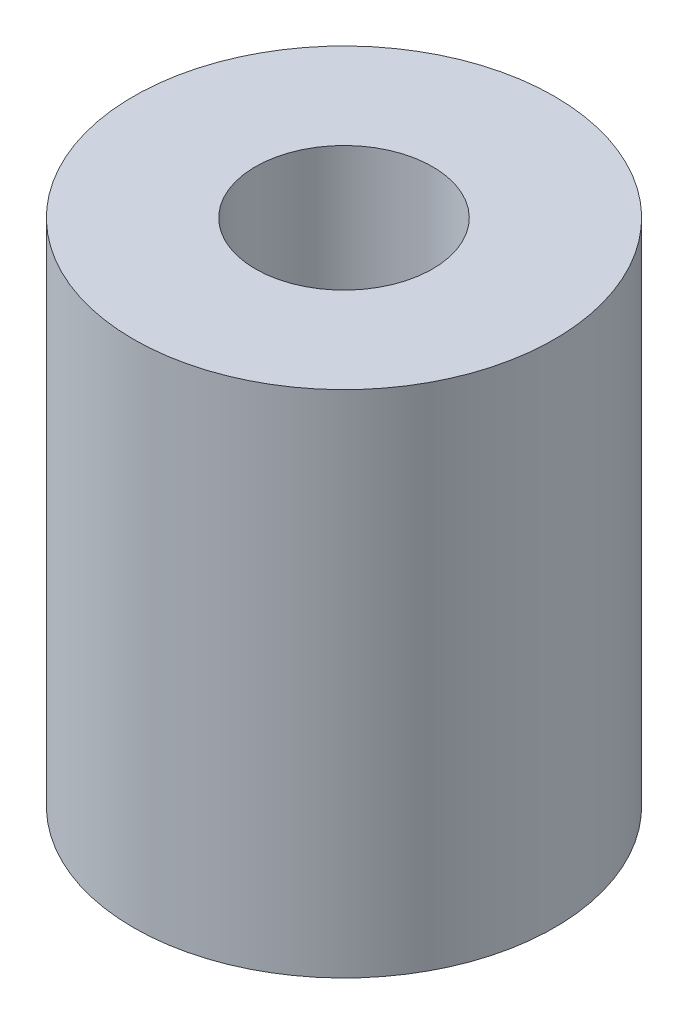
SolidWorks part; units mm, degrees
ref_plane "Front Plane" through (0, 0, 0) normal (0, 0, 1) x (1, 0, 0)
ref_plane "Top Plane" through (0, 0, 0) normal (0, 1, 0) x (1, 0, 0)
ref_plane "Right Plane" through (0, 0, 0) normal (1, 0, 0) x (0, 0, -1)
sketch "Sketch1" plane through (0, 0, 0) normal (0, 1, 0) x (1, 0, 0)
  circle A0 centre (0, 0) radius 9.5
  circle A1 centre (0, 0) radius 2.5
  dimension "D1" = 19
  dimension "D2" = 5
extrude "Boss-Extrude1" add sketch "Sketch1" along normal blind 23
sketch "Sketch2" plane through (0, 23, 0) normal (0, 1, 0) x (1, 0, 0)
  circle A0 centre (0, 0) radius 4
  dimension "D1" = 8
extrude "Cut-Extrude1" cut sketch "Sketch2" against normal blind 12
